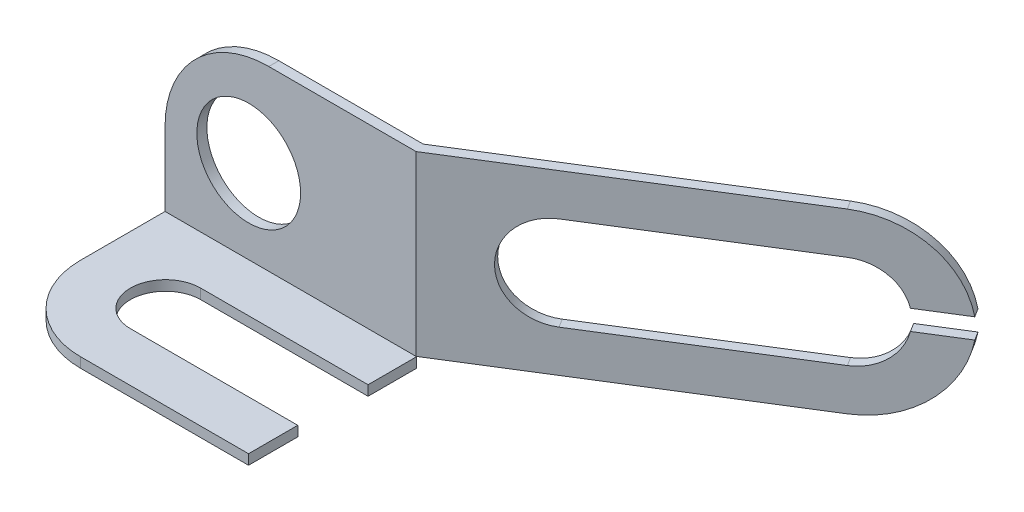
SolidWorks part; units mm, degrees
ref_plane "Front Plane" through (0, 0, 0) normal (0, 0, 1) x (1, 0, 0)
ref_plane "Top Plane" through (0, 0, 0) normal (0, 1, 0) x (1, 0, 0)
ref_plane "Right Plane" through (0, 0, 0) normal (1, 0, 0) x (0, 0, -1)
sketch "Sketch1" plane through (0, 0, 0) normal (0, 1, 0) x (1, 0, 0)
  line L3 (-0.0031, -0.5041) -> (1, -0.5041)
  line L4 (0, -0.21) -> (1, -0.21)
  line L5 (0, 0.21) -> (1, 0.21)
  line L6 (0.9969, 0) -> (-0.5031, 0) construction
  line L8 (1, 0.5) -> (-0.5031, 0.5)
  line L9 (1, 0.5) -> (1, 0.21)
  line L10 (1, -0.21) -> (1, -0.5041)
  line L11 (-0.5031, -0.0041) -> (-0.5031, 0.5)
  arc A0 (0, 0.21) -> (0, -0.21) centre (0, 0) ccw
  arc A1 (-0.0031, -0.5041) -> (-0.5031, -0.0041) centre (-0.0031, -0.0041) cw
  dimension "D1" = 0.42
  dimension "D4" = 0.5
  dimension "D7" = 0.21
  dimension "D16" = 0.5
  dimension "D2" = 1
  dimension "D3" = 1
  dimension "D5" = 0.21
  dimension "D8" = 1.5031
  dimension "D9" = 0.29
  dimension "D10" = 0.2941
  dimension "D11" = 1.0031
  dimension "D13" = 0.5041
  dimension "D15" = 0.21
ref_plane "Plane1" through (0, 0, -0.5) normal (0, 0, 1) x (1, 0, 0)
sketch "Sketch2" plane through (0, 0, -0.5) normal (0, 0, 1) x (1, 0, 0)
  line L0 (-0.5031, 0) -> (-0.5031, 0.44)
  line L1 (1, 0) -> (-0.5031, 0) construction
  line L2 (-0.0031, 0) -> (-0.5031, 0) construction
  line L3 (0.1169, 0.53) -> (3.1846, 0.53) construction
  line L4 (-0.5031, 0) -> (0.9969, 0)
  line L5 (0.9969, 1.06) -> (0.9969, 0)
  line L6 (0.1169, 1.06) -> (0.9969, 1.06)
  arc A1 (-0.5031, 0.44) -> (0.1169, 1.06) centre (0.1169, 0.44) cw
  circle A3 centre (-0.0031, 0.5) radius 0.31
  point P16 (-0.5031, 1.06)
  dimension "D1" = 1.06
  dimension "D3" = 0.53
  dimension "D4" = 0.53
  dimension "D6" = 1.5
  dimension "D5" = 1.06
  dimension "D7" = 0.62
  dimension "D8" = 0.62
  dimension "D2" = 1.06
  dimension "D9" = 0.5
  dimension "D10" = 0.56
  dimension "D11" = 0.5
ref_plane "Plane2" through (0.0553, 0, 0.0884) normal (0.5299, 0, 0.848) x (0, -1, 0)
sketch "Sketch3" plane through (0.0553, 0, 0.0884) normal (0.5299, 0, 0.848) x (0, -1, 0)
  line L0 (-1.06, 1.1104) -> (-1.06, 2.9804)
  line L1 (0, 1.1104) -> (0, 2.9804)
  line L2 (-0.53, 1.1104) -> (-0.53, 2.9804) construction
  line L4 (-0.47, 1.1104) -> (-0.47, 2.9804) construction
  line L5 (-0.53, 1.7304) -> (-0.53, 2.9804) construction
  line L6 (-0.81, 1.7304) -> (-0.81, 2.9804)
  line L7 (-0.25, 1.7304) -> (-0.25, 2.9804)
  line L8 (-1.06, 1.1104) -> (0, 1.1104) construction
  line L9 (-0.59, 1.1104) -> (-0.59, 2.9804) construction
  line L10 (-0.59, 3.5331) -> (-0.59, 3.2539)
  line L11 (-0.47, 3.2539) -> (-0.47, 3.5331)
  line L12 (-1.06, 1.1104) -> (0, 1.1104)
  arc A0 (-0.81, 1.7304) -> (-0.25, 1.7304) centre (-0.53, 1.7304) ccw
  arc A1 (-0.25, 2.9804) -> (-0.47, 3.2539) centre (-0.53, 2.9804) ccw
  arc A2 (-0.59, 3.2539) -> (-0.81, 2.9804) centre (-0.53, 2.9804) ccw
  arc A3 (-1.06, 2.9804) -> (-0.59, 3.5331) centre (-0.5, 2.9804) cw
  arc A4 (0, 2.9804) -> (-0.47, 3.5331) centre (-0.56, 2.9804) ccw
  point P16 (-0.1601, 0.9523)
  point P17 (-0.1601, 3.3823)
  point P18 (-0.8401, 0.9523)
  point P19 (-0.8401, 3.3823)
  dimension "D9" = 2.1435
  dimension "D10" = 1.25
  dimension "D2" = 0.28
  dimension "D3" = 1.06
  dimension "D12" = 0.62
  dimension "D14" = 1.87
  dimension "D6" = 0.28
  dimension "D16" = 0.56
  dimension "D17" = 0.56
  dimension "D1" = 0.53
  dimension "D4" = 0.62
  dimension "D5" = 1.25
  dimension "D11" = 0.62
  dimension "D7" = 0.06
  dimension "D8" = 0.06
  dimension "D13" = 1.25
  dimension "D15" = 1.87
extrude "Boss-Extrude3" add sketch "Sketch1" against normal blind 0.06
extrude "Boss-Extrude4" add sketch "Sketch2" against normal blind 0.06 separate body
extrude "Boss-Extrude5" add sketch "Sketch3" against normal blind 0.06
